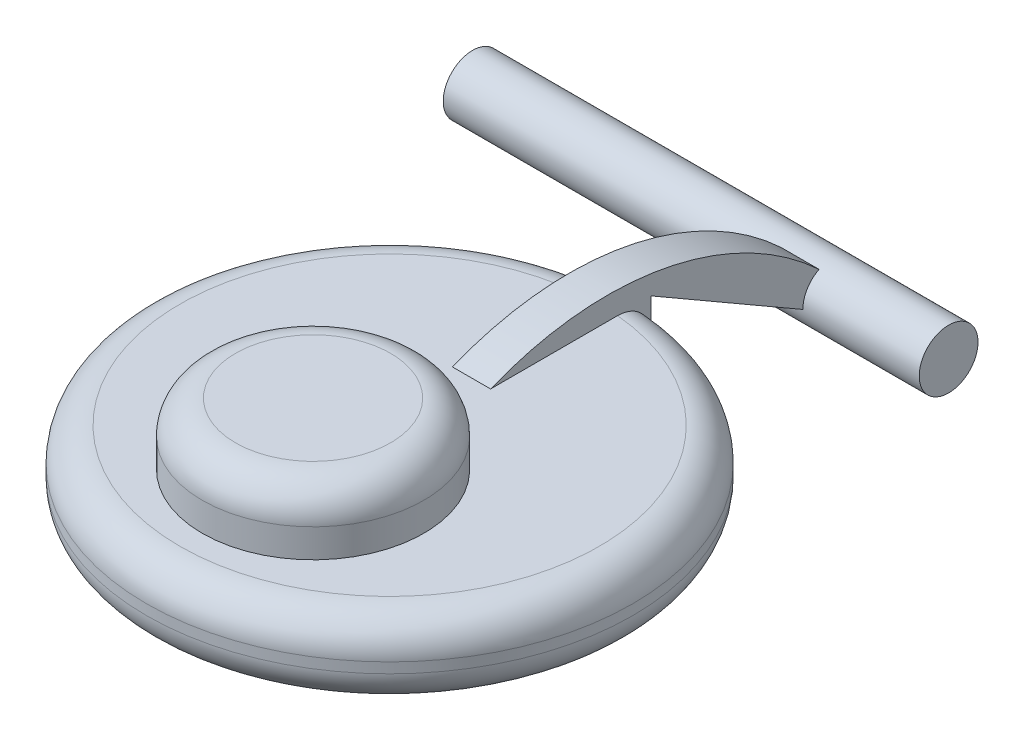
SolidWorks part; units mm, degrees
material "6061 Alloy"
ref_plane "Front Plane" through (0, 0, 0) normal (0, 0, 1) x (1, 0, 0)
ref_plane "Top Plane" through (0, 0, 0) normal (0, 1, 0) x (1, 0, 0)
ref_plane "Right Plane" through (0, 0, 0) normal (1, 0, 0) x (0, 0, -1)
sketch "Sketch1" plane through (0, 0, 0) normal (1, 0, 0) x (0, 0, -1)
  circle A0 centre (0, 0) radius 2.2479
  dimension "D1" = 4.4958
extrude "Boss-Extrude1" add sketch "Sketch1" along normal blind 36.3982
ref_plane "Plane1" through (27.5082, 0, 0) normal (1, 0, 0) x (0, 0, -1)
sketch "Sketch2" plane through (27.5082, 0, 0) normal (1, 0, 0) x (0, 0, -1)
  line L0 (0, -1.3345) -> (-13.8141, 6.6411)
  line L1 (0, 2.4727) -> (0, -2.4727) construction
  line L2 (2.4727, 0) -> (-2.4727, 0) construction
  line L3 (-13.8141, 6.6411) -> (-26.1331, 6.6411)
  line L4 (0, 0.9951) -> (0, -1.3345)
  arc A0 (-26.1331, 6.6411) -> (0, 0.9951) centre (-17.2046, -15.3351) cw
  point P9 (0, 0)
  dimension "D4" = 23.7208
  dimension "D1" = 15.9512
  dimension "D2" = 30
  dimension "D3" = 12.319
extrude "Boss-Extrude2" add sketch "Sketch2" against normal blind 2.921
sketch "Sketch3" plane through (0, 6.6411, 0) normal (0, -1, 0) x (1, 0, 0)
  line L0 (26.0477, 26.1331) -> (26.0477, 13.8141) construction
  line L1 (24.5872, 26.1331) -> (27.5082, 26.1331) construction
  line L2 (24.5872, 13.8141) -> (27.5082, 13.8141) construction
  circle A0 centre (26.0477, 32.3942) radius 18.5801
  point P8 (26.0477, 34.3615)
  dimension "D1" = 37.1602
extrude "Boss-Extrude3" add sketch "Sketch3" along normal blind 5.8674
fillet "Fillet1" radius 2.54 2 edges at (26.0477, 0.7737, 13.8141) (26.0477, 6.6411, 50.9743)
sketch "Sketch4" plane through (0, 6.6411, 0) normal (0, 1, 0) x (1, 0, 0)
  line L0 (26.0477, -26.1331) -> (26.0477, -48.4343) construction
  line L1 (24.5872, -26.1331) -> (27.5082, -26.1331) construction
  arc A0 (24.5872, -16.4208) -> (27.5082, -16.4208) centre (26.0477, -32.3942) ccw construction
  circle A1 centre (26.0477, -38.2485) radius 8.4709
  point P9 (26.0477, -38.2485)
  point P10 (0, 0)
  dimension "D1" = 16.9418
extrude "Boss-Extrude4" add sketch "Sketch4" along normal blind 4.7244
fillet "Fillet2" radius 2.54 1 edges at (26.0477, 11.3655, 46.7194)
